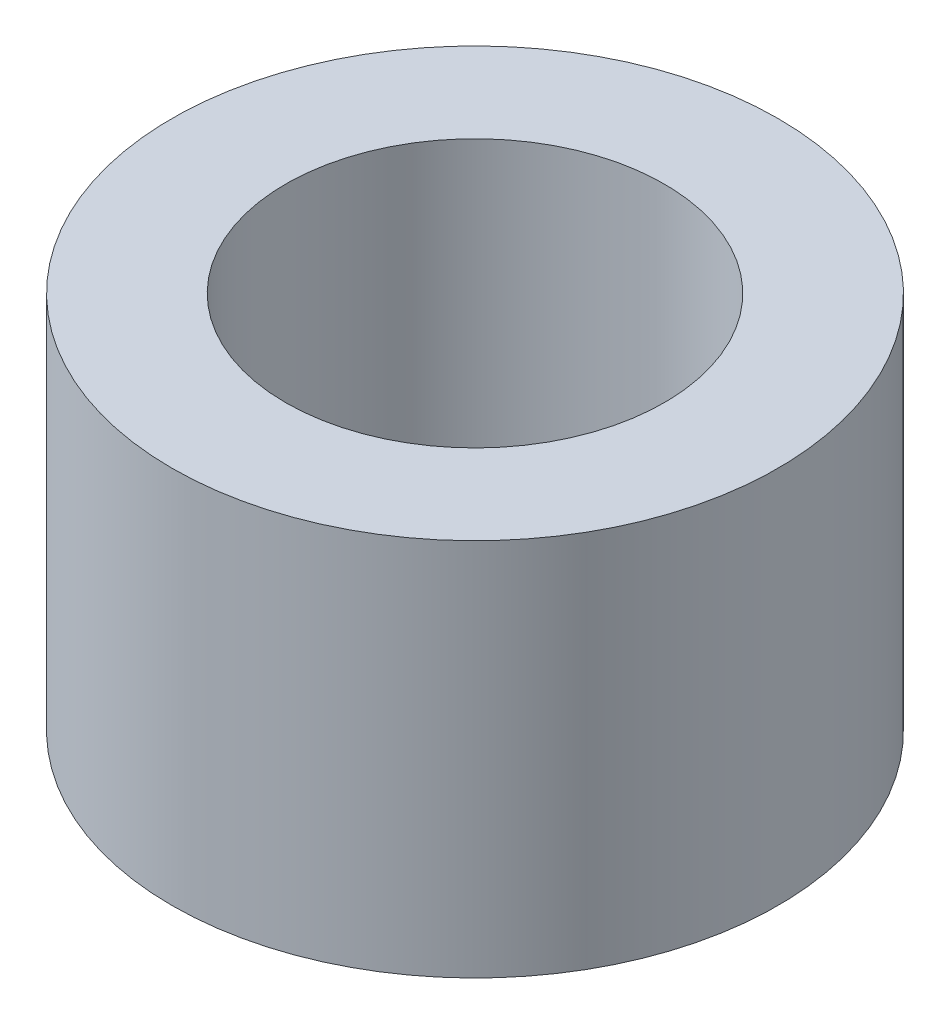
SolidWorks part; units mm, degrees
ref_plane "Front Plane" through (0, 0, 0) normal (0, 0, 1) x (1, 0, 0)
ref_plane "Top Plane" through (0, 0, 0) normal (0, 1, 0) x (1, 0, 0)
ref_plane "Right Plane" through (0, 0, 0) normal (1, 0, 0) x (0, 0, -1)
sketch "Sketch1" plane through (0, 0, 0) normal (0, 1, 0) x (1, 0, 0)
  circle A0 centre (0, 0) radius 4
  circle A1 centre (0, 0) radius 2.5
  dimension "D1" = 5
  dimension "D2" = 8
extrude "Boss-Extrude1" add sketch "Sketch1" along normal blind 5
